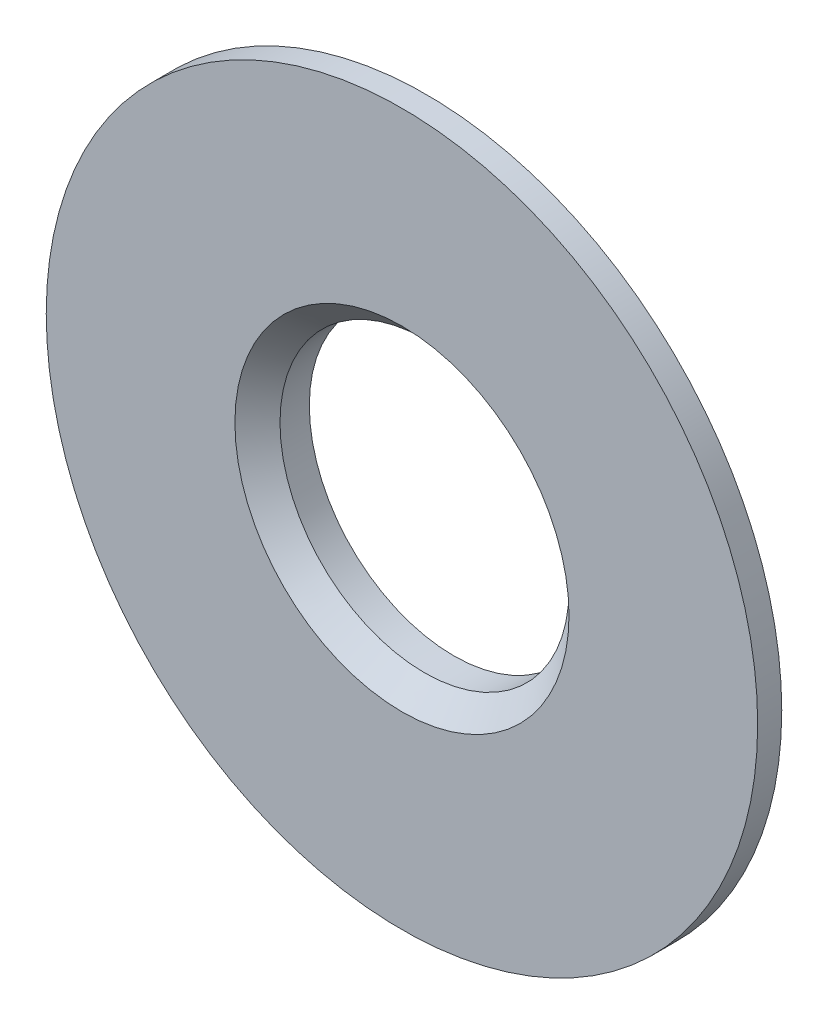
SolidWorks part; units mm, degrees
material "AISI Type 316L stainless steel"
ref_plane "Front Plane" through (0, 0, 0) normal (0, 0, 1) x (1, 0, 0)
ref_plane "Top Plane" through (0, 0, 0) normal (0, 1, 0) x (1, 0, 0)
ref_plane "Right Plane" through (0, 0, 0) normal (1, 0, 0) x (0, 0, -1)
sketch "Sketch1" plane through (0, 0, 0) normal (1, 0, 0) x (0, 0, -1)
  line L0 (0, 0) -> (-48.5527, 0) construction
  line L1 (0, 16) -> (-3, 16)
  line L2 (-3, 16) -> (-5.2, 18.2)
  line L3 (-5.2, 18.2) -> (-5.2, 38)
  line L4 (-5.2, 38) -> (-3, 38)
  dimension "D1" = 32
  dimension "D2" = 76
  dimension "D3" = 2.2
  dimension "D4" = 2.2
  dimension "D5" = 5.2
  dimension "D6" = 45
revolve "Revolve-Thin1" add sketch "Sketch1" angle 360 about L0 wall 0.4
